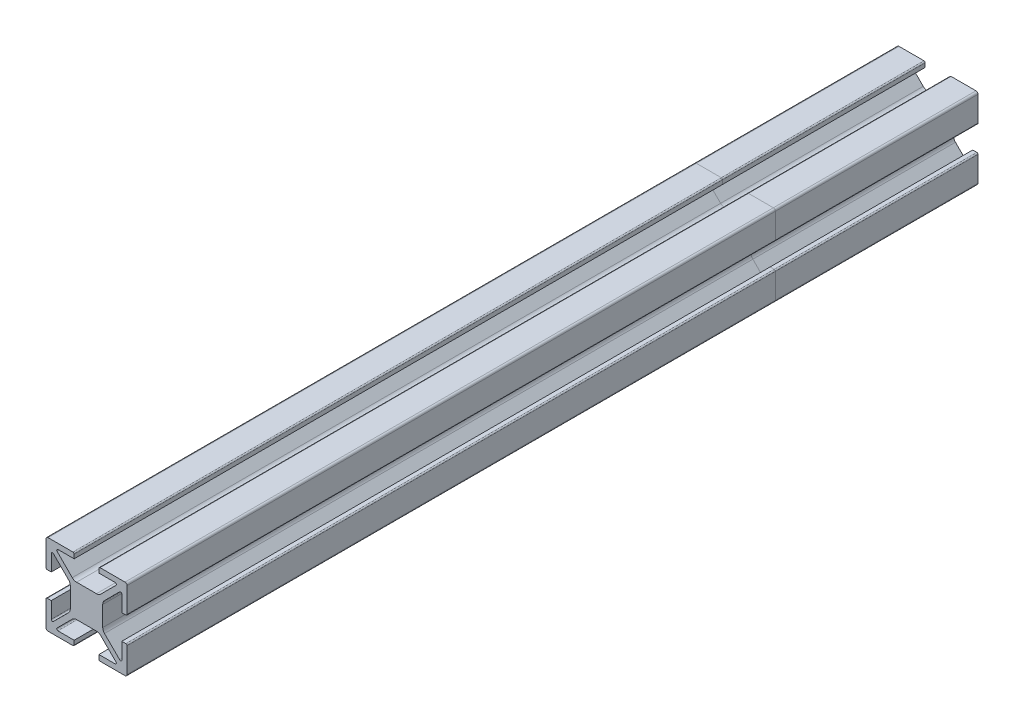
SolidWorks part; units mm, degrees
material "6063-T5"
material "6063-T5"
ref_plane "Front" through (0, 0, 0) normal (0, 0, 1) x (1, 0, 0)
ref_plane "Top" through (0, 0, 0) normal (0, 1, 0) x (1, 0, 0)
ref_plane "Right" through (0, 0, 0) normal (1, 0, 0) x (0, 0, -1)
sketch "Esboço1" plane through (0, 0, 0) normal (1, 0, 0) x (0, 0, -1)
  line L0 (0, 0) -> (-50, 0)
  dimension "D1" = 50
other "Quadrado PF20-21 - PERFIL 2020 T-SLOT 6MM(1)"
ref_plane "Plano1" through (0, 0, 0) normal (0, 0, 1) x (0, -1, 0)
sketch "Esboço11" plane through (0, 0, 0) normal (0, 0, 1) x (0, -1, 0)
  line L0 (8.1879, -7.2686) -> (4.4393, -3.5201)
  line L1 (4, -2.4594) -> (4, 2.4594)
  line L2 (4.4393, 3.5201) -> (8.1879, 7.2686)
  line L3 (8.7, 7.0565) -> (8.7, 3.05)
  line L4 (10, 3.35) -> (10, 9.5)
  line L5 (9.5, 10) -> (3.35, 10)
  line L6 (3.05, 8.7) -> (7.0565, 8.7)
  line L7 (7.2686, 8.1879) -> (3.5201, 4.4393)
  line L8 (2.4594, 4) -> (-2.4594, 4)
  line L9 (-3.5201, 4.4393) -> (-7.2686, 8.1879)
  line L10 (-7.0565, 8.7) -> (-3.05, 8.7)
  line L11 (-3.35, 10) -> (-9.5, 10)
  line L12 (-10, 9.5) -> (-10, 3.35)
  line L13 (-8.7, 3.05) -> (-8.7, 7.0565)
  line L14 (-8.1879, 7.2686) -> (-4.4393, 3.5201)
  line L15 (-4, 2.4594) -> (-4, -2.4594)
  line L16 (-4.4393, -3.5201) -> (-8.1879, -7.2686)
  line L17 (-8.7, -7.0565) -> (-8.7, -3.05)
  line L18 (-10, -3.35) -> (-10, -9.5)
  line L19 (-9.5, -10) -> (-3.35, -10)
  line L20 (-3.05, -8.7) -> (-7.0565, -8.7)
  line L21 (-7.2686, -8.1879) -> (-3.5201, -4.4393)
  line L22 (-2.4594, -4) -> (2.4594, -4)
  line L23 (3.5201, -4.4393) -> (7.2686, -8.1879)
  line L24 (7.0565, -8.7) -> (3.05, -8.7)
  line L25 (3.05, -8.7) -> (3.05, -9.7)
  line L26 (3.35, -10) -> (9.5, -10)
  line L27 (10, -9.5) -> (10, -3.35)
  line L28 (8.7, -3.05) -> (9.7, -3.05)
  line L29 (8.7, -3.05) -> (8.7, -7.0565)
  line L30 (-3.05, 9.7) -> (-3.05, 8.7)
  line L31 (-9.7, -3.05) -> (-8.7, -3.05)
  line L32 (3.05, 9.7) -> (3.05, 8.7)
  line L33 (-9.7, 3.05) -> (-8.7, 3.05)
  line L34 (-3.05, -8.7) -> (-3.05, -9.7)
  line L35 (8.7, 3.05) -> (9.7, 3.05)
  circle A0 centre (0, 0) radius 2.25
  arc A1 (8.1879, -7.2686) -> (8.7, -7.0565) centre (8.4, -7.0565) ccw
  arc A2 (4, -2.4594) -> (4.4393, -3.5201) centre (5.5, -2.4594) ccw
  arc A3 (4.4393, 3.5201) -> (4, 2.4594) centre (5.5, 2.4594) ccw
  arc A4 (8.7, 7.0565) -> (8.1879, 7.2686) centre (8.4, 7.0565) ccw
  arc A5 (10, 9.5) -> (9.5, 10) centre (9.5, 9.5) ccw
  arc A6 (7.2686, 8.1879) -> (7.0565, 8.7) centre (7.0565, 8.4) ccw
  arc A7 (2.4594, 4) -> (3.5201, 4.4393) centre (2.4594, 5.5) ccw
  arc A8 (-3.5201, 4.4393) -> (-2.4594, 4) centre (-2.4594, 5.5) ccw
  arc A9 (-7.0565, 8.7) -> (-7.2686, 8.1879) centre (-7.0565, 8.4) ccw
  arc A10 (-9.5, 10) -> (-10, 9.5) centre (-9.5, 9.5) ccw
  arc A11 (-8.1879, 7.2686) -> (-8.7, 7.0565) centre (-8.4, 7.0565) ccw
  arc A12 (-4, 2.4594) -> (-4.4393, 3.5201) centre (-5.5, 2.4594) ccw
  arc A13 (-4.4393, -3.5201) -> (-4, -2.4594) centre (-5.5, -2.4594) ccw
  arc A14 (-8.7, -7.0565) -> (-8.1879, -7.2686) centre (-8.4, -7.0565) ccw
  arc A15 (-10, -9.5) -> (-9.5, -10) centre (-9.5, -9.5) ccw
  arc A16 (-7.2686, -8.1879) -> (-7.0565, -8.7) centre (-7.0565, -8.4) ccw
  arc A17 (-2.4594, -4) -> (-3.5201, -4.4393) centre (-2.4594, -5.5) ccw
  arc A18 (3.5201, -4.4393) -> (2.4594, -4) centre (2.4594, -5.5) ccw
  arc A19 (7.0565, -8.7) -> (7.2686, -8.1879) centre (7.0565, -8.4) ccw
  arc A20 (9.5, -10) -> (10, -9.5) centre (9.5, -9.5) ccw
  arc A21 (-9.7, 3.05) -> (-10, 3.35) centre (-9.7, 3.35) cw
  arc A22 (-9.7, -3.05) -> (-10, -3.35) centre (-9.7, -3.35) ccw
  arc A23 (-3.05, -9.7) -> (-3.35, -10) centre (-3.35, -9.7) cw
  arc A24 (3.05, -9.7) -> (3.35, -10) centre (3.35, -9.7) ccw
  arc A25 (9.7, -3.05) -> (10, -3.35) centre (9.7, -3.35) cw
  arc A26 (9.7, 3.05) -> (10, 3.35) centre (9.7, 3.35) ccw
  arc A27 (3.05, 9.7) -> (3.35, 10) centre (3.35, 9.7) cw
  arc A28 (-3.05, 9.7) -> (-3.35, 10) centre (-3.35, 9.7) ccw
  point P0 (0, 10)
  point P1 (-10, 10)
  point P2 (0, 0)
  point P3 (10, 10)
  point P4 (10, 0)
  point P5 (10, -10)
  point P6 (0, -10)
  point P7 (-10, -10)
  point P8 (-10, 0)
  point P9 (0, 0)
  point P88 (0, 0)
sketch "Croquis1" plane through (0, 0, 50) normal (0, 0, 1) x (1, 0, 0)
  line L36 (-7.2686, -8.1879) -> (-3.5201, -4.4393)
  line L37 (-2.4594, -4) -> (2.4594, -4)
  line L38 (3.5201, -4.4393) -> (7.2686, -8.1879)
  line L39 (7.0565, -8.7) -> (3.05, -8.7)
  line L40 (3.05, -8.7) -> (3.05, -9.7)
  line L41 (3.35, -10) -> (9.5, -10)
  line L42 (10, -9.5) -> (10, -3.35)
  line L43 (9.7, -3.05) -> (8.7, -3.05)
  line L44 (8.7, -3.05) -> (8.7, -7.0565)
  line L45 (8.1879, -7.2686) -> (4.4393, -3.5201)
  line L46 (4, -2.4594) -> (4, 2.4594)
  line L47 (4.4393, 3.5201) -> (8.1879, 7.2686)
  line L48 (8.7, 7.0565) -> (8.7, 3.05)
  line L49 (8.7, 3.05) -> (9.7, 3.05)
  line L50 (10, 3.35) -> (10, 9.5)
  line L51 (9.5, 10) -> (3.35, 10)
  line L52 (3.05, 9.7) -> (3.05, 8.7)
  line L53 (3.05, 8.7) -> (7.0565, 8.7)
  line L54 (7.2686, 8.1879) -> (3.5201, 4.4393)
  line L55 (2.4594, 4) -> (-2.4594, 4)
  line L56 (-3.5201, 4.4393) -> (-7.2686, 8.1879)
  line L57 (-7.0565, 8.7) -> (-3.05, 8.7)
  line L58 (-3.05, 8.7) -> (-3.05, 9.7)
  line L59 (-3.35, 10) -> (-9.5, 10)
  line L60 (-10, 9.5) -> (-10, 3.35)
  line L61 (-9.7, 3.05) -> (-8.7, 3.05)
  line L62 (-8.7, 3.05) -> (-8.7, 7.0565)
  line L63 (-8.1879, 7.2686) -> (-4.4393, 3.5201)
  line L64 (-4, 2.4594) -> (-4, -2.4594)
  line L65 (-4.4393, -3.5201) -> (-8.1879, -7.2686)
  line L66 (-8.7, -7.0565) -> (-8.7, -3.05)
  line L67 (-8.7, -3.05) -> (-9.7, -3.05)
  line L68 (-10, -3.35) -> (-10, -9.5)
  line L69 (-9.5, -10) -> (-3.35, -10)
  line L70 (-3.05, -9.7) -> (-3.05, -8.7)
  line L71 (-3.05, -8.7) -> (-7.0565, -8.7)
  line L72 (-7.2686, -8.1879) -> (-3.5201, -4.4393)
  line L73 (-2.4594, -4) -> (2.4594, -4)
  line L74 (3.5201, -4.4393) -> (7.2686, -8.1879)
  line L75 (7.0565, -8.7) -> (3.05, -8.7)
  line L76 (3.05, -8.7) -> (3.05, -9.7)
  line L77 (3.35, -10) -> (9.5, -10)
  line L78 (10, -9.5) -> (10, -3.35)
  line L79 (9.7, -3.05) -> (8.7, -3.05)
  line L80 (8.7, -3.05) -> (8.7, -7.0565)
  line L81 (8.1879, -7.2686) -> (4.4393, -3.5201)
  line L82 (4, -2.4594) -> (4, 2.4594)
  line L83 (4.4393, 3.5201) -> (8.1879, 7.2686)
  line L84 (8.7, 7.0565) -> (8.7, 3.05)
  line L85 (8.7, 3.05) -> (9.7, 3.05)
  line L86 (10, 3.35) -> (10, 9.5)
  line L87 (9.5, 10) -> (3.35, 10)
  line L88 (3.05, 9.7) -> (3.05, 8.7)
  line L89 (3.05, 8.7) -> (7.0565, 8.7)
  line L90 (7.2686, 8.1879) -> (3.5201, 4.4393)
  line L91 (2.4594, 4) -> (-2.4594, 4)
  line L92 (-3.5201, 4.4393) -> (-7.2686, 8.1879)
  line L93 (-7.0565, 8.7) -> (-3.05, 8.7)
  line L94 (-3.05, 8.7) -> (-3.05, 9.7)
  line L95 (-3.35, 10) -> (-9.5, 10)
  line L96 (-10, 9.5) -> (-10, 3.35)
  line L97 (-9.7, 3.05) -> (-8.7, 3.05)
  line L98 (-8.7, 3.05) -> (-8.7, 7.0565)
  line L99 (-8.1879, 7.2686) -> (-4.4393, 3.5201)
  line L100 (-4, 2.4594) -> (-4, -2.4594)
  line L101 (-4.4393, -3.5201) -> (-8.1879, -7.2686)
  line L102 (-8.7, -7.0565) -> (-8.7, -3.05)
  line L103 (-8.7, -3.05) -> (-9.7, -3.05)
  line L104 (-10, -3.35) -> (-10, -9.5)
  line L105 (-9.5, -10) -> (-3.35, -10)
  line L106 (-3.05, -9.7) -> (-3.05, -8.7)
  line L107 (-3.05, -8.7) -> (-7.0565, -8.7)
  arc A28 (-7.2686, -8.1879) -> (-7.0565, -8.7) centre (-7.0565, -8.4) ccw
  arc A29 (-2.4594, -4) -> (-3.5201, -4.4393) centre (-2.4594, -5.5) ccw
  arc A30 (3.5201, -4.4393) -> (2.4594, -4) centre (2.4594, -5.5) ccw
  arc A31 (7.0565, -8.7) -> (7.2686, -8.1879) centre (7.0565, -8.4) ccw
  arc A32 (3.05, -9.7) -> (3.35, -10) centre (3.35, -9.7) ccw
  arc A33 (9.5, -10) -> (10, -9.5) centre (9.5, -9.5) ccw
  arc A34 (10, -3.35) -> (9.7, -3.05) centre (9.7, -3.35) ccw
  arc A35 (8.1879, -7.2686) -> (8.7, -7.0565) centre (8.4, -7.0565) ccw
  arc A36 (4, -2.4594) -> (4.4393, -3.5201) centre (5.5, -2.4594) ccw
  arc A37 (4.4393, 3.5201) -> (4, 2.4594) centre (5.5, 2.4594) ccw
  arc A38 (8.7, 7.0565) -> (8.1879, 7.2686) centre (8.4, 7.0565) ccw
  arc A39 (9.7, 3.05) -> (10, 3.35) centre (9.7, 3.35) ccw
  arc A40 (10, 9.5) -> (9.5, 10) centre (9.5, 9.5) ccw
  arc A41 (3.35, 10) -> (3.05, 9.7) centre (3.35, 9.7) ccw
  arc A42 (7.2686, 8.1879) -> (7.0565, 8.7) centre (7.0565, 8.4) ccw
  arc A43 (2.4594, 4) -> (3.5201, 4.4393) centre (2.4594, 5.5) ccw
  arc A44 (-3.5201, 4.4393) -> (-2.4594, 4) centre (-2.4594, 5.5) ccw
  arc A45 (-7.0565, 8.7) -> (-7.2686, 8.1879) centre (-7.0565, 8.4) ccw
  arc A46 (-3.05, 9.7) -> (-3.35, 10) centre (-3.35, 9.7) ccw
  arc A47 (-9.5, 10) -> (-10, 9.5) centre (-9.5, 9.5) ccw
  arc A48 (-10, 3.35) -> (-9.7, 3.05) centre (-9.7, 3.35) ccw
  arc A49 (-8.1879, 7.2686) -> (-8.7, 7.0565) centre (-8.4, 7.0565) ccw
  arc A50 (-4, 2.4594) -> (-4.4393, 3.5201) centre (-5.5, 2.4594) ccw
  arc A51 (-4.4393, -3.5201) -> (-4, -2.4594) centre (-5.5, -2.4594) ccw
  arc A52 (-8.7, -7.0565) -> (-8.1879, -7.2686) centre (-8.4, -7.0565) ccw
  arc A53 (-9.7, -3.05) -> (-10, -3.35) centre (-9.7, -3.35) ccw
  arc A54 (-10, -9.5) -> (-9.5, -10) centre (-9.5, -9.5) ccw
  arc A55 (-3.35, -10) -> (-3.05, -9.7) centre (-3.35, -9.7) ccw
  arc A56 (-7.2686, -8.1879) -> (-7.0565, -8.7) centre (-7.0565, -8.4) ccw
  arc A57 (-2.4594, -4) -> (-3.5201, -4.4393) centre (-2.4594, -5.5) ccw
  arc A58 (3.5201, -4.4393) -> (2.4594, -4) centre (2.4594, -5.5) ccw
  arc A59 (7.0565, -8.7) -> (7.2686, -8.1879) centre (7.0565, -8.4) ccw
  arc A60 (3.05, -9.7) -> (3.35, -10) centre (3.35, -9.7) ccw
  arc A61 (9.5, -10) -> (10, -9.5) centre (9.5, -9.5) ccw
  arc A62 (10, -3.35) -> (9.7, -3.05) centre (9.7, -3.35) ccw
  arc A63 (8.1879, -7.2686) -> (8.7, -7.0565) centre (8.4, -7.0565) ccw
  arc A64 (4, -2.4594) -> (4.4393, -3.5201) centre (5.5, -2.4594) ccw
  arc A65 (4.4393, 3.5201) -> (4, 2.4594) centre (5.5, 2.4594) ccw
  arc A66 (8.7, 7.0565) -> (8.1879, 7.2686) centre (8.4, 7.0565) ccw
  arc A67 (9.7, 3.05) -> (10, 3.35) centre (9.7, 3.35) ccw
  arc A68 (10, 9.5) -> (9.5, 10) centre (9.5, 9.5) ccw
  arc A69 (3.35, 10) -> (3.05, 9.7) centre (3.35, 9.7) ccw
  arc A70 (7.2686, 8.1879) -> (7.0565, 8.7) centre (7.0565, 8.4) ccw
  arc A71 (2.4594, 4) -> (3.5201, 4.4393) centre (2.4594, 5.5) ccw
  arc A72 (-3.5201, 4.4393) -> (-2.4594, 4) centre (-2.4594, 5.5) ccw
  arc A73 (-7.0565, 8.7) -> (-7.2686, 8.1879) centre (-7.0565, 8.4) ccw
  arc A74 (-3.05, 9.7) -> (-3.35, 10) centre (-3.35, 9.7) ccw
  arc A75 (-9.5, 10) -> (-10, 9.5) centre (-9.5, 9.5) ccw
  arc A76 (-10, 3.35) -> (-9.7, 3.05) centre (-9.7, 3.35) ccw
  arc A77 (-8.1879, 7.2686) -> (-8.7, 7.0565) centre (-8.4, 7.0565) ccw
  arc A78 (-4, 2.4594) -> (-4.4393, 3.5201) centre (-5.5, 2.4594) ccw
  arc A79 (-4.4393, -3.5201) -> (-4, -2.4594) centre (-5.5, -2.4594) ccw
  arc A80 (-8.7, -7.0565) -> (-8.1879, -7.2686) centre (-8.4, -7.0565) ccw
  arc A81 (-9.7, -3.05) -> (-10, -3.35) centre (-9.7, -3.35) ccw
  arc A82 (-10, -9.5) -> (-9.5, -10) centre (-9.5, -9.5) ccw
  arc A83 (-3.35, -10) -> (-3.05, -9.7) centre (-3.35, -9.7) ccw
  dimension "D1" = 0
extrude "Saliente-Extruir1" add sketch "Croquis1" along normal blind 160 separate body
